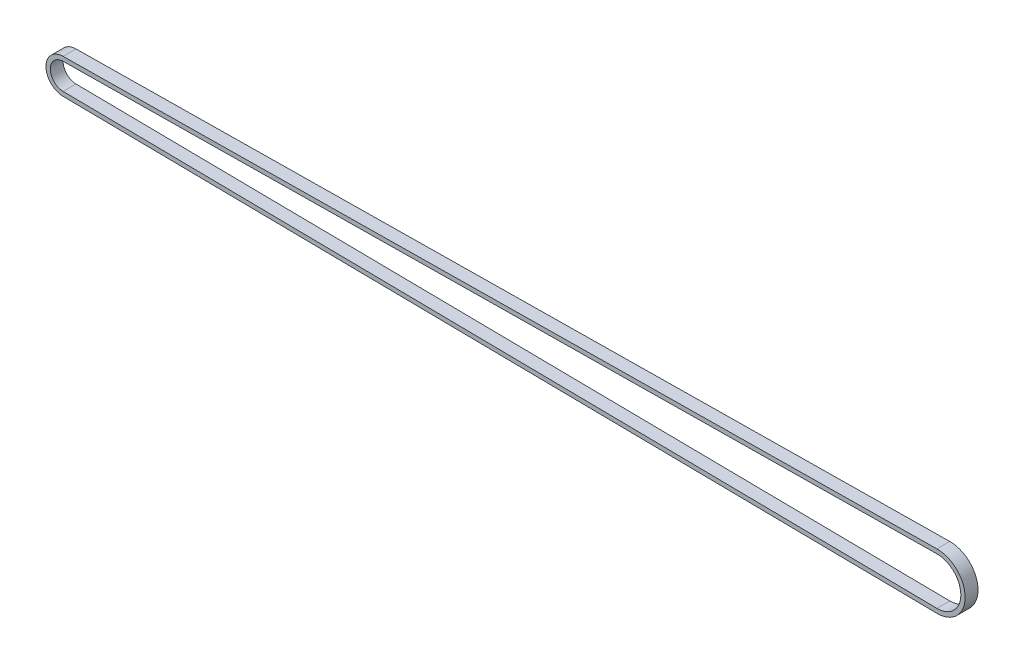
SolidWorks part; units mm, degrees
ref_plane "Front Plane" through (0, 0, 0) normal (0, 0, 1) x (1, 0, 0)
ref_plane "Top Plane" through (0, 0, 0) normal (0, 1, 0) x (1, 0, 0)
ref_plane "Right Plane" through (0, 0, 0) normal (1, 0, 0) x (0, 0, -1)
sketch "Sketch2" plane through (0, 0, 0) normal (0, 0, 1) x (1, 0, 0)
  line L0 (0, 0) -> (1, 0) construction
  line L1 (0, 0) -> (0, 1) construction
  line L2 (406.874, -12.1053) -> (-0.0875, -7.0695)
  line L3 (-0.0838, 7.0695) -> (406.8802, 11.8929)
  arc A0 (406.8802, 11.8929) -> (406.874, -12.1053) centre (407.0225, -0.1063) cw
  arc A1 (-0.0875, -7.0695) -> (-0.0838, 7.0695) centre (0, 0) cw
extrude "Extrude-Thin1" add sketch "Sketch2" along normal mid plane 6 thin thin type mid plane wall 2
